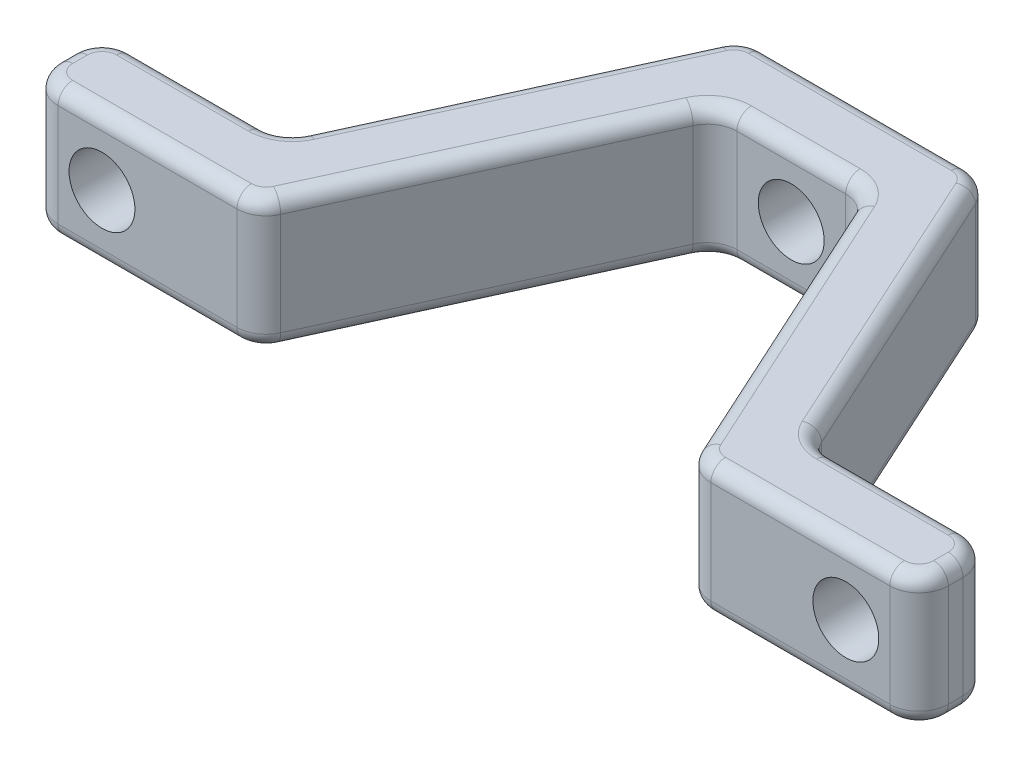
SolidWorks part; units mm, degrees
ref_plane "Front Plane" through (0, 0, 0) normal (0, 0, 1) x (1, 0, 0)
ref_plane "Top Plane" through (0, 0, 0) normal (0, 1, 0) x (1, 0, 0)
ref_plane "Right Plane" through (0, 0, 0) normal (1, 0, 0) x (0, 0, -1)
sketch "Sketch1" plane through (0, 0, 0) normal (0, 1, 0) x (1, 0, 0)
  line L7 (0, 0) -> (8.2125, 0)
  line L8 (0, 0) -> (-8.2125, 0)
  line L9 (-8.2125, 0) -> (-20.4, -26.67)
  line L10 (8.2125, 0) -> (20.4, -26.67)
  line L11 (-20.4, -26.67) -> (20.4, -26.67)
  line L12 (-14.9027, -26.67) -> (-5, -5)
  line L13 (-5, -5) -> (5, -5)
  line L14 (5, -5) -> (14.9027, -26.67)
  line L15 (-20.4, -26.67) -> (-30.4, -26.67)
  line L16 (-30.4, -26.67) -> (-30.4, -21.67)
  line L17 (-30.4, -21.67) -> (-18.1151, -21.67)
  line L18 (20.4, -26.67) -> (30.4, -26.67)
  line L19 (30.4, -26.67) -> (30.4, -21.67)
  line L20 (30.4, -21.67) -> (18.1151, -21.67)
  point P0 (0, 0)
  point P10 (-25.4, -26.67)
  point P19 (25.4, -26.67)
  point P20 (0, 0)
  dimension "D1" = 10
  dimension "D2" = 26.67
  dimension "D3" = 5
  dimension "D4" = 10
  dimension "D5" = 5
  dimension "D6" = 50.8
  dimension "D7" = 5
  dimension "D8" = 5
extrude "Boss-Extrude1" add sketch "Sketch1" along normal blind 9 contours L13 L14 L11 L10 L7 L8 L9 L12 | L17 L16 L15 L9 | L19 L20 L10 L18
sketch "Sketch2" plane through (0, 0, 0) normal (0, 0, 1) x (1, 0, 0)
  line L4 (-8.2125, 0) -> (8.2125, 0)
  line L5 (-8.2125, 9) -> (-8.2125, 0)
  line L6 (8.2125, 9) -> (-8.2125, 9)
  line L7 (8.2125, 0) -> (8.2125, 9)
  line L8 (-8.2125, 0) -> (8.2125, 0)
  line L9 (-8.2125, 9) -> (-8.2125, 0)
  line L10 (8.2125, 9) -> (-8.2125, 9)
  line L11 (8.2125, 0) -> (8.2125, 9)
  circle A0 centre (0, 4.5) radius 2.25
  circle A1 centre (-25.4, 4.5) radius 2.25
  circle A2 centre (25.4, 4.5) radius 2.25
  point P8 (0, 9)
  point P10 (0, 0)
  point P12 (0, 0)
  dimension "D2" = 4.5
  dimension "D3" = 4.5
  dimension "D4" = 25.4
  dimension "D5" = 25.4
  dimension "D1" = 0
extrude "Cut-Extrude1" cut sketch "Sketch2" along normal up to next contours A0 | A2 | A1
fillet "Fillet1" radius 2 12 edges at (-5, 4.5, 5) (-14.9027, 4.5, 26.67) (-30.4, 4.5, 26.67) (-30.4, 4.5, 21.67) (-18.1151, 4.5, 21.67) (-8.2125, 4.5, 0) (8.2125, 4.5, 0) (18.1151, 4.5, 21.67) (30.4, 4.5, 21.67) (30.4, 4.5, 26.67) (14.9027, 4.5, 26.67) (5, 4.5, 5)
fillet "Fillet2" radius 1 48 edges at (-8.0086, 0, 0.3174) (-13.1638, 0, 10.835) (-18.319, 0, 21.3526) (-23.9001, 0, 21.67) (-29.8142, 0, 22.2558) (-30.4, 0, 24.17) (-29.8142, 0, 26.0842) (-22.2938, 0, 26.67) (-15.1066, 0, 26.3526) (-9.9513, 0, 15.835) (-4.7961, 0, 5.3174) (0, 0, 5) (4.7961, 0, 5.3174) (9.9513, 0, 15.835) (15.1066, 0, 26.3526) (22.2938, 0, 26.67) (29.8142, 0, 26.0842) (30.4, 0, 24.17) (29.8142, 0, 22.2558) (23.9001, 0, 21.67) (18.319, 0, 21.3526) (13.1638, 0, 10.835) (8.0086, 0, 0.3174) (-8.0086, 9, 0.3174) (-13.1638, 9, 10.835) (-18.319, 9, 21.3526) (-23.9001, 9, 21.67) (-29.8142, 9, 22.2558) (-30.4, 9, 24.17) (-29.8142, 9, 26.0842) (-22.2938, 9, 26.67) (-15.1066, 9, 26.3526) (-9.9513, 9, 15.835) (-4.7961, 9, 5.3174) (0, 9, 5) (4.7961, 9, 5.3174) (9.9513, 9, 15.835) (15.1066, 9, 26.3526) (22.2938, 9, 26.67) (29.8142, 9, 26.0842) (30.4, 9, 24.17) (29.8142, 9, 22.2558) (23.9001, 9, 21.67) (18.319, 9, 21.3526) (13.1638, 9, 10.835) (8.0086, 9, 0.3174) (0, 0, 0) (0, 9, 0)
